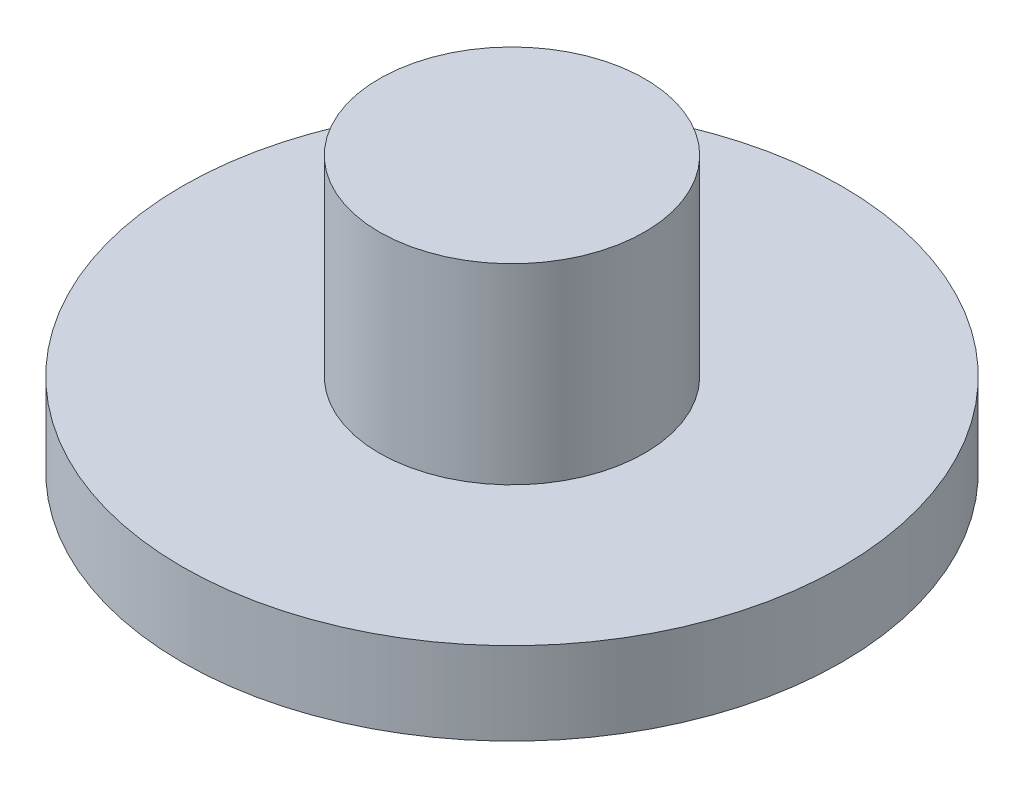
SolidWorks part; units mm, degrees
material "201 Annealed Stainless Steel (SS)"
ref_plane "Front Plane" through (0, 0, 0) normal (0, 0, 1) x (1, 0, 0)
ref_plane "Top Plane" through (0, 0, 0) normal (0, 1, 0) x (1, 0, 0)
ref_plane "Right Plane" through (0, 0, 0) normal (1, 0, 0) x (0, 0, -1)
sketch "Sketch1" plane through (0, 0, 0) normal (0, 1, 0) x (1, 0, 0)
  circle A0 centre (0, 0) radius 7.575
  dimension "D1" = 15.15
extrude "Boss-Extrude1" add sketch "Sketch1" along normal blind 1.9
sketch "Sketch2" plane through (0, 1.9, 0) normal (0, 1, 0) x (1, 0, 0)
  circle A0 centre (0, 0) radius 3.05
  dimension "D1" = 6.1
extrude "Boss-Extrude2" add sketch "Sketch2" along normal blind 4.4
